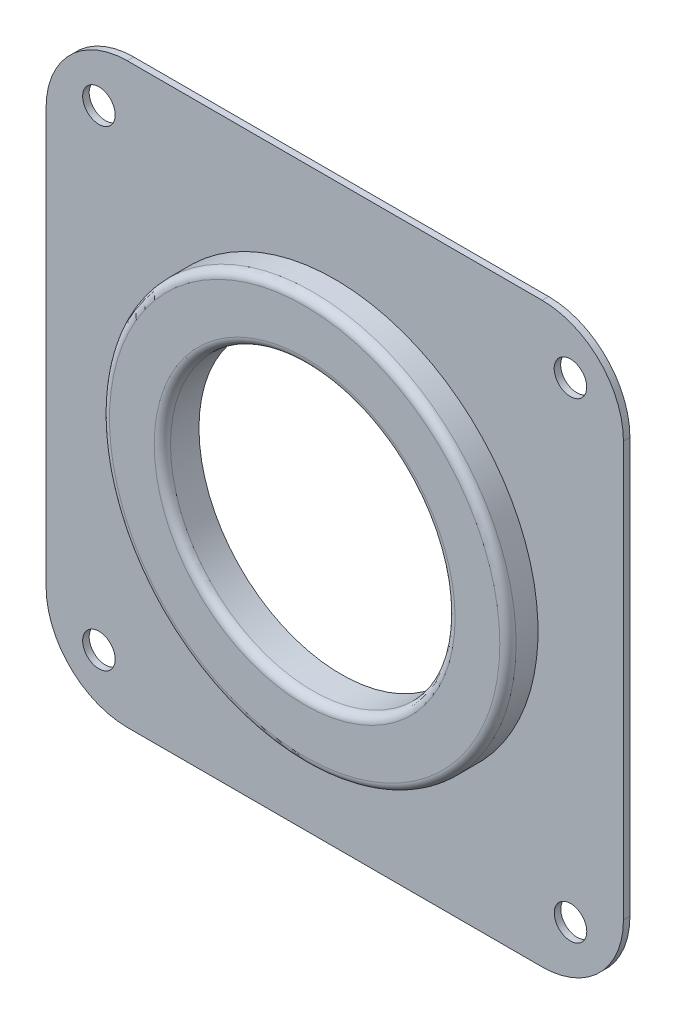
SolidWorks part; units mm, degrees
ref_plane "前视基准面" through (0, 0, 0) normal (0, 0, 1) x (1, 0, 0)
ref_plane "上视基准面" through (0, 0, 0) normal (0, 1, 0) x (1, 0, 0)
ref_plane "右视基准面" through (0, 0, 0) normal (1, 0, 0) x (0, 0, -1)
ref_plane "基准面1" through (0, 0, 1) normal (0, 0, 1) x (1, 0, 0)
sketch "草图1" plane through (0, 0, 1) normal (0, 0, 1) x (1, 0, 0)
  line L0 (-35.5, 35.5) -> (-35.5, -35.5)
  line L1 (-35.5, -35.5) -> (35.5, -35.5)
  line L2 (35.5, -35.5) -> (35.5, 35.5)
  line L3 (35.5, 35.5) -> (-35.5, 35.5)
extrude "凸台-拉伸1" add sketch "草图1" against normal blind 0.8
ref_plane "基准面2" through (0, 0, 0) normal (0, -1, 0) x (1, 0, 0)
sketch "草图2" plane through (0, 0, 0) normal (0, -1, 0) x (1, 0, 0)
  line L0 (25, 4.7) -> (0, 4.7)
  line L1 (0, 4.7) -> (0, 1)
  line L2 (0, 1) -> (25, 1)
  line L3 (25, 1) -> (25, 4.7)
  line L4 (0, 4.7) -> (0, 1) construction
  dimension "D1" = 3.7
revolve "旋转1" add sketch "草图2" angle 360 about L4
hole_wizard "M30 间隙孔1" positions "草图4" profile "草图3" hole size "M30" standard "ANSI Metric"
sketch "草图4" plane through (0, 0, 4.7) normal (0, 0, 1) x (1, 0, 0)
  point P0 (0, 0)
sketch "草图3" plane through (0, 0, 4.7) normal (1, 0, 0) x (0, -1, 0)
  line L0 (0, 0) -> (0, 4.5)
  line L1 (0, 4.5) -> (17.5, 4.5)
  line L2 (17.5, 4.5) -> (17.5, 0)
  line L5 (17.5, 0) -> (0, 0)
  line L11 (0, -6.35) -> (0, 107.95) construction
  dimension "通孔孔直径" = 35
  dimension "通孔孔深度" = 4.5
hole_wizard "Ø4.0 (4) 直径孔1" positions "草图6" profile "草图5" hole size "Ø4.0" standard "ANSI Metric" end condition through all
sketch "草图6" plane through (0, 0, 1) normal (0, 0, 1) x (1, 0, 0)
  point P0 (-29, 28.98)
  point P1 (-29, -29)
  point P2 (28.9928, -28.9928)
  point P3 (28.9828, 28.9828)
  dimension "D1" = 82
  dimension "D2" = 82
sketch "草图5" plane through (-29, 28.98, 1) normal (1, 0, 0) x (0, -1, 0)
  line L0 (0, 0) -> (0, 0.8)
  line L1 (0, 0.8) -> (2, 0.8)
  line L2 (2, 0.8) -> (2, 0)
  line L5 (2, 0) -> (0, 0)
  line L11 (0, -6.35) -> (0, 107.95) construction
  dimension "通孔孔直径" = 4
  dimension "通孔孔深度" = 0.8
fillet "圆角1" radius 1 2 edges at (17.5, 0, 4.7) (-25, 0, 4.7)
fillet "圆角2" radius 10 4 edges at (35.5, -35.5, 0.6) (-35.5, -35.5, 0.6) (-35.5, 35.5, 0.6) (35.5, 35.5, 0.6)
